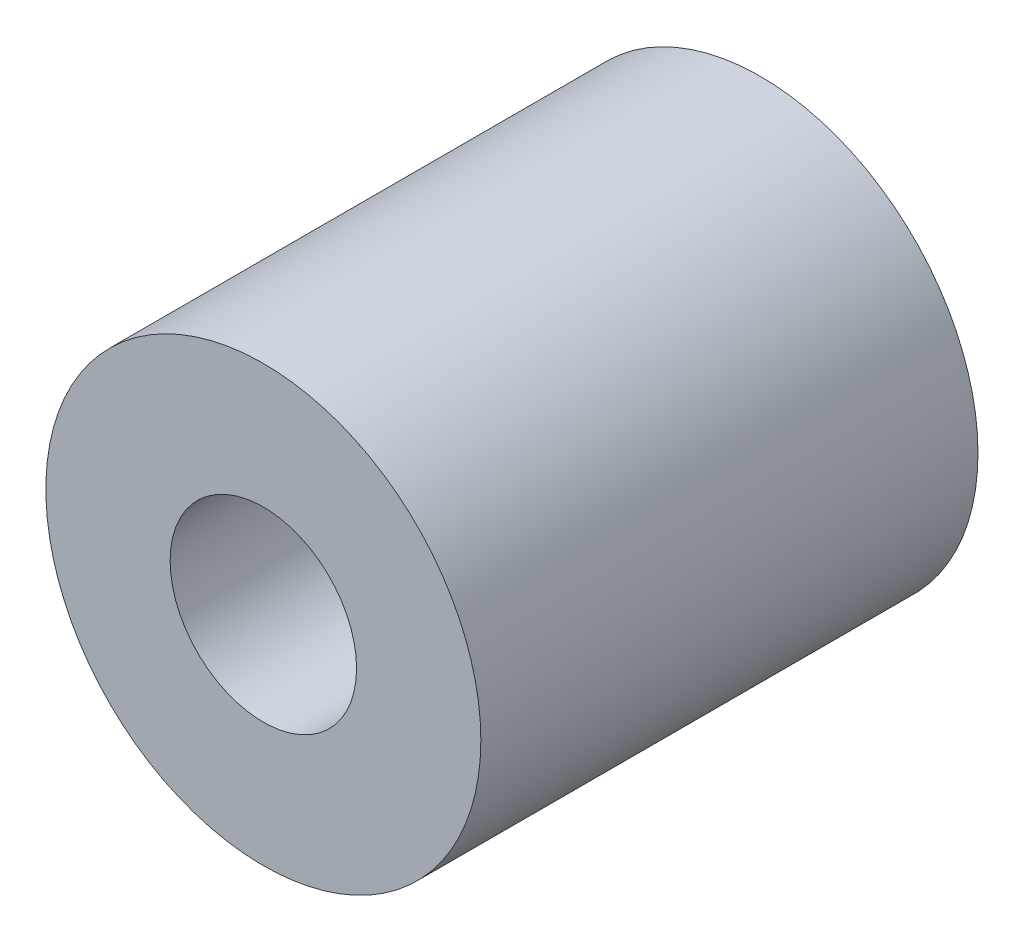
SolidWorks part; units mm, degrees
material "Brass"
ref_plane "Front Plane" through (0, 0, 0) normal (0, 0, 1) x (1, 0, 0)
ref_plane "Top Plane" through (0, 0, 0) normal (0, 1, 0) x (1, 0, 0)
ref_plane "Right Plane" through (0, 0, 0) normal (1, 0, 0) x (0, 0, -1)
sketch "Sketch1" plane through (0, 0, 0) normal (0, 0, 1) x (1, 0, 0)
  circle A0 centre (0, 0) radius 4.7625
  circle A1 centre (0, 0) radius 11.1125
  dimension "D1" = 22.225
  dimension "D2" = 9.525
extrude "Boss-Extrude1" add sketch "Sketch1" along normal mid plane 25.4
